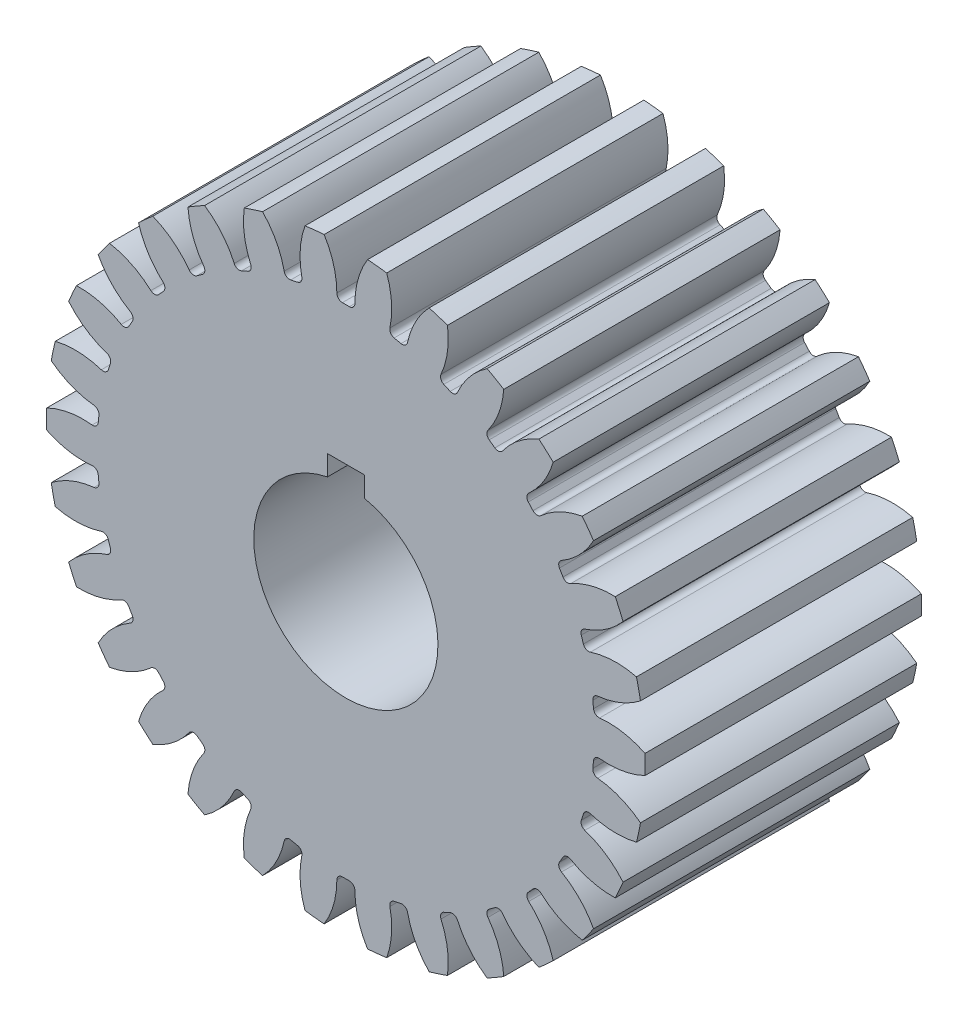
SolidWorks part; units mm, degrees
ref_plane "Front Plane" through (0, 0, 0) normal (0, 0, 1) x (1, 0, 0)
ref_plane "Top Plane" through (0, 0, 0) normal (0, 1, 0) x (1, 0, 0)
ref_plane "Right Plane" through (0, 0, 0) normal (1, 0, 0) x (0, 0, -1)
sketch "Sketch1" plane through (0, 0, 0) normal (0, 0, 1) x (1, 0, 0)
  circle A0 centre (0, 0) radius 32.5
  dimension "D1" = 65
extrude "Boss-Extrude1" add sketch "Sketch1" along normal mid plane 30
sketch "Sketch2" plane through (0, 0, 15) normal (0, 0, 1) x (1, 0, 0)
  line L0 (0, 0) -> (0, 10) construction
  line L2 (-2, 12) -> (2, 12)
  line L3 (-2, 12) -> (-2, 9.798)
  line L5 (2, 12) -> (2, 9.798)
  line L6 (-2, 12) -> (2, 8) construction
  line L7 (-2, 8) -> (2, 12) construction
  arc A0 (-2, 9.798) -> (2, 9.798) centre (0, 0) ccw
  dimension "D1" = 20
  dimension "D2" = 4
extrude "Cut-Extrude1" cut sketch "Sketch2" against normal through all
sketch "Sketch3" plane through (0, 0, -15) normal (0, 0, -1) x (-1, 0, 0)
  circle A0 centre (0, 0) radius 15
  circle A1 centre (0, 0) radius 25
  dimension "D1" = 50
  dimension "D2" = 30
extrude "Cut-Extrude2" cut sketch "Sketch3" against normal blind 6
sketch "Sketch4" plane through (0, 0, -15) normal (0, 0, -1) x (-1, 0, 0)
  line L0 (0, 0) -> (0, 40.6046) construction
  line L1 (-0.3801, 27) -> (0.3801, 27)
  arc A0 (0.9801, 27.6001) -> (3.15, 33.5) centre (10.0801, 27.6022) cw
  arc A1 (-0.9801, 27.6001) -> (-3.15, 33.5) centre (-10.0801, 27.6022) ccw
  arc A2 (-3.15, 33.5) -> (3.15, 33.5) centre (0, 49.1869) ccw
  arc A3 (0.3801, 27) -> (0.9801, 27.6001) centre (0.3801, 27.6) ccw
  arc A4 (-0.9801, 27.6001) -> (-0.3801, 27) centre (-0.3801, 27.6) ccw
  point P8 (0, 27)
  point P13 (1, 27)
  point P16 (-1, 27)
  dimension "D5" = 9.1
  dimension "D6" = 16
  dimension "D7" = 0.6
  dimension "D1" = 1
  dimension "D2" = 27
  dimension "D3" = 6.5
  dimension "D4" = 3.15
extrude "Cut-Extrude3" cut sketch "Sketch4" against normal through all both and the other way through all
pattern_circular "CirPattern1" count 30 over 360 about axis through (0, 0, 0) along (0, 0, 1) of "Cut-Extrude3"
